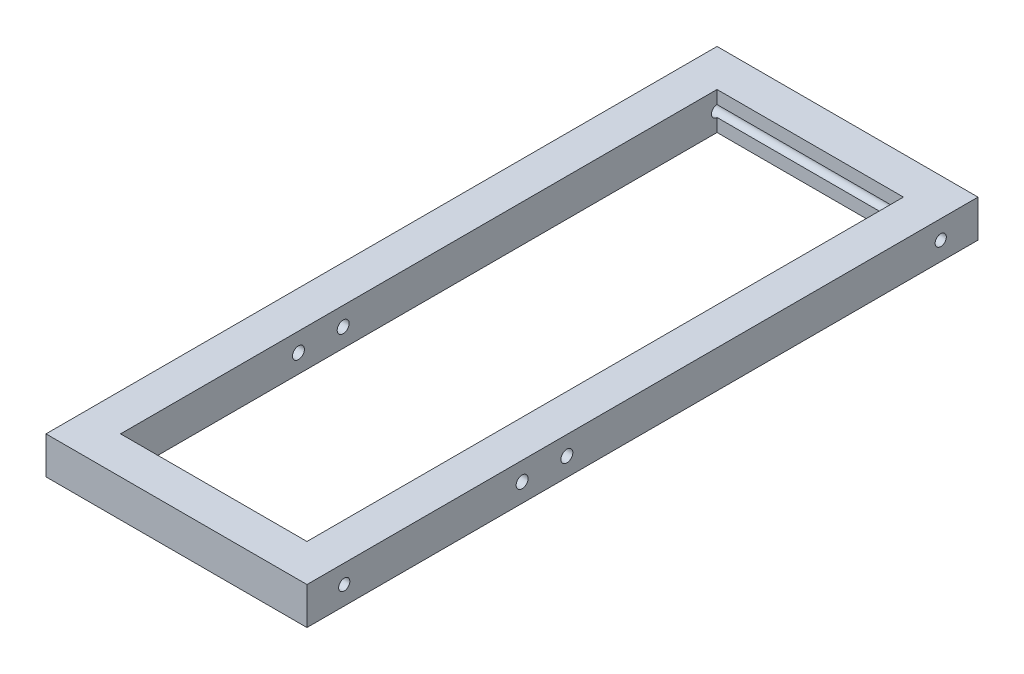
SolidWorks part; units mm, degrees
ref_plane "Alzado" through (0, 0, 0) normal (0, 0, 1) x (1, 0, 0)
ref_plane "Planta" through (0, 0, 0) normal (0, 1, 0) x (1, 0, 0)
ref_plane "Vista lateral" through (0, 0, 0) normal (1, 0, 0) x (0, 0, -1)
sketch "Croquis1" plane through (0, 0, 0) normal (0, 1, 0) x (1, 0, 0)
  line L0 (-25, -80) -> (-25, 80)
  line L1 (-35, -90) -> (35, -90)
  line L2 (-35, -90) -> (-35, 90)
  line L3 (-35, 90) -> (35, 90)
  line L4 (35, -90) -> (35, 90)
  line L5 (-35, -90) -> (35, 90) construction
  line L6 (-35, 90) -> (35, -90) construction
  line L7 (-25, 80) -> (25, 80)
  line L8 (25, -80) -> (25, 80)
  line L9 (-25, -80) -> (25, -80)
  point P0 (0, 0)
  dimension "D1" = 70
  dimension "D2" = 180
  dimension "D3" = 10
extrude "Saliente-Extruir1" add sketch "Croquis1" along normal mid plane 10
sketch "Croquis2" plane through (0, 0, 0) normal (1, 0, 0) x (0, 0, -1)
  line L0 (88.4837, 0) -> (-88.6655, 0) construction
  line L1 (-90, 5) -> (-90, -5) construction
  line L2 (0, 28.4135) -> (0, -21.8934) construction
  circle A0 centre (-80, 0) radius 1.5
  circle A1 centre (80, 0) radius 1.5
  dimension "D1" = 3
  dimension "D2" = 10
extrude "Cortar-Extruir1" cut sketch "Croquis2" against normal mid plane 120
hole_wizard "Taladro de margen para M31" positions "Croquis3D1" profile "Croquis3" hole size "M3" standard "ISO" end condition through all
sketch3d "Croquis3D1"
  point P0 (-35, -0.0109, 32.2875)
  point P2 (-35, -0.003, 20.2858)
sketch "Croquis3" plane through (-35, -0.0109, 32.2875) normal (0, 1, 0) x (0, 0, 1)
  line L0 (0, 0) -> (0, 70)
  line L1 (0, 70) -> (1.6, 70)
  line L2 (1.6, 70) -> (1.6, 0)
  line L5 (1.6, 0) -> (0, 0)
  line L11 (0, -6.35) -> (0, 107.95) construction
  dimension "Diámetro de taladro hasta el siguiente" = 3.2
  dimension "Profundidad de taladro hasta el siguiente" = 70
sketch "Croquis4" plane through (35, 0, 0) normal (1, 0, 0) x (0, 0, -1)
  line L4 (-90, -5) -> (90, -5)
  line L5 (90, -5) -> (90, 5)
  line L6 (90, 5) -> (-90, 5)
  line L7 (-90, 5) -> (-90, -5)
  line L8 (-90, -5) -> (90, -5)
  line L9 (90, -5) -> (90, 5)
  line L10 (90, 5) -> (-90, 5)
  line L11 (-90, 5) -> (-90, -5)
  circle A0 centre (-80, 0) radius 1.5 construction
  circle A1 centre (-80, 0) radius 1.5
  circle A2 centre (80, 0) radius 1.5 construction
  circle A3 centre (80, 0) radius 1.5
  dimension "D2" = 10
  dimension "D1" = 0
